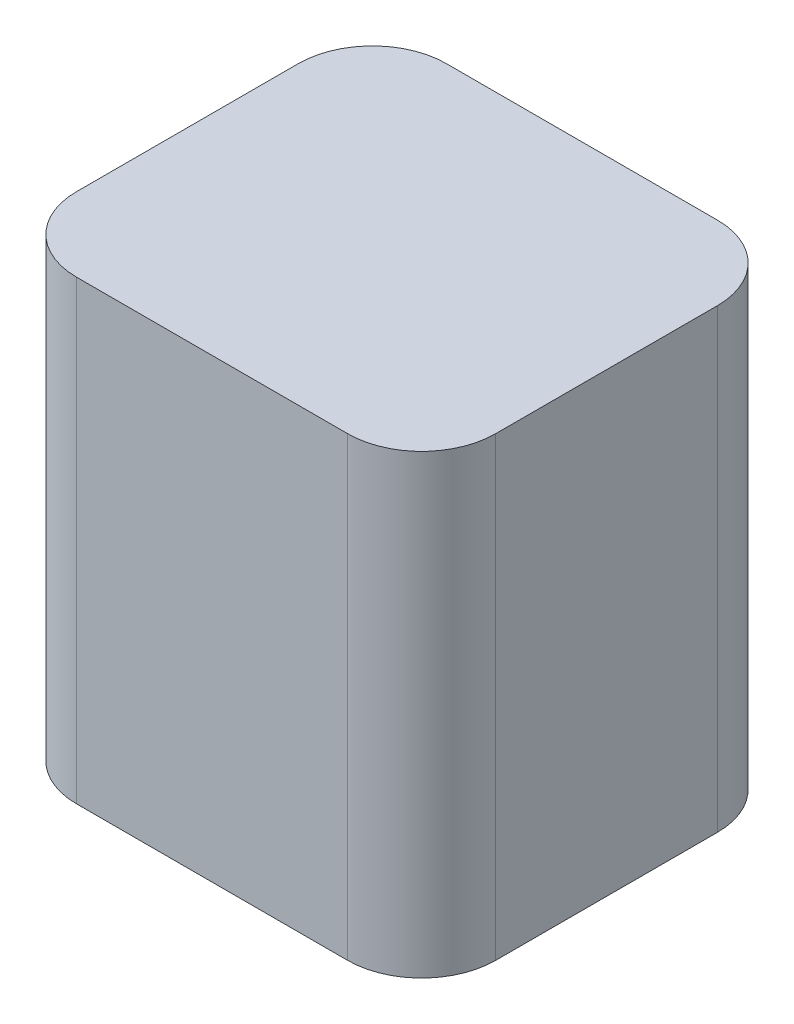
SolidWorks part; units mm, degrees
ref_plane "Front" through (0, 0, 0) normal (0, 0, 1) x (1, 0, 0)
ref_plane "Top" through (0, 0, 0) normal (0, 1, 0) x (1, 0, 0)
ref_plane "Right" through (0, 0, 0) normal (1, 0, 0) x (0, 0, -1)
sketch "Sketch1" plane through (0, 0, 0) normal (0, 1, 0) x (1, 0, 0)
  line L1 (-431.8, 381) -> (431.8, 381)
  line L2 (-431.8, 381) -> (-431.8, -381)
  line L3 (-431.8, -381) -> (431.8, -381)
  line L4 (431.8, 381) -> (431.8, -381)
  line L5 (-431.8, 381) -> (431.8, -381) construction
  line L6 (-431.8, -381) -> (431.8, 381) construction
  point P0 (0, 0)
  dimension "D1" = 863.6
  dimension "D2" = 762
extrude "Boss-Extrude1" add sketch "Sketch1" along normal blind 939.8
fillet "Fillet1" radius 152.4 4 edges at (-431.8, 469.9, -381) (431.8, 469.9, -381) (431.8, 469.9, 381) (-431.8, 469.9, 381)
